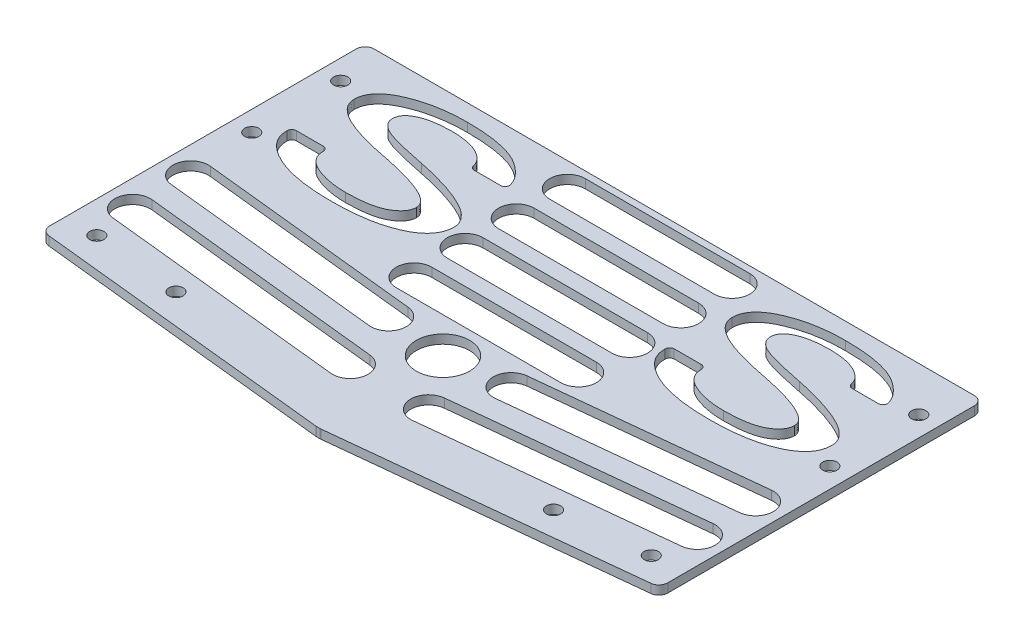
SolidWorks part; units mm, degrees
material "Thornel Mat VMA"
ref_plane "前视基准面" through (0, 0, 0) normal (0, 0, 1) x (1, 0, 0)
ref_plane "上视基准面" through (0, 0, 0) normal (0, 1, 0) x (1, 0, 0)
ref_plane "右视基准面" through (0, 0, 0) normal (1, 0, 0) x (0, 0, -1)
other "Configuration Table"
sketch "草图1" plane through (0, 0, 0) normal (0, 1, 0) x (1, 0, 0)
  line L1 (-69.5, 40) -> (69.5, 40)
  line L2 (-69.5, 40) -> (-69.5, -40)
  line L3 (-69.5, -40) -> (69.5, -40)
  line L4 (69.5, 40) -> (69.5, -40)
  line L5 (-69.5, 40) -> (69.5, -40) construction
  line L6 (-69.5, -40) -> (69.5, 40) construction
  point P0 (0, 0)
  dimension "D1" = 139
  dimension "D2" = 80
extrude "凸台-拉伸1" add sketch "草图1" along normal blind 2
sketch "草图2" plane through (0, 2, 0) normal (0, 1, 0) x (1, 0, 0)
  line L0 (0.5, -40) -> (69.5, -32.7478)
  line L1 (-69.5, -40) -> (69.5, -40) construction
  line L2 (69.5, -40) -> (69.5, 40) construction
  line L3 (69.5, -32.7478) -> (69.5, -40)
  line L4 (69.5, -40) -> (0.5, -40)
  line L5 (-69.5, -40) -> (-0.5, -40)
  line L6 (-0.5, -40) -> (-69.5, -32.7478)
  line L7 (-69.5, 40) -> (-69.5, -40) construction
  line L8 (-69.5, -32.7478) -> (-69.5, -40)
  dimension "D1" = 6
  dimension "D2" = 69
extrude "切除-拉伸1" cut sketch "草图2" against normal through all
sketch "草图3" plane through (0, 2, 0) normal (0, 1, 0) x (1, 0, 0)
  circle A0 centre (62.3465, -27.5028) radius 1.6
  circle A1 centre (42.456, -29.5934) radius 1.6
  circle A2 centre (-42.456, -29.5934) radius 1.6
  circle A3 centre (-62.3465, -27.5028) radius 1.6
  dimension "D1" = 3.2
extrude "切除-拉伸2" cut sketch "草图3" against normal blind 10
sketch "草图4" plane through (0, 2, 0) normal (0, 1, 0) x (1, 0, 0)
  line L0 (0, -45.4013) -> (0, 45.8413) construction
  line L1 (-63.5, -18.2958) -> (-8.8013, -24.0449) construction
  line L2 (-63.0819, -14.3177) -> (-8.3832, -20.0668)
  line L3 (-63.9181, -22.2739) -> (-9.2194, -28.023)
  line L4 (-63.5, -5.2242) -> (-13.7739, -10.4506) construction
  line L5 (-63.0819, -1.2461) -> (-13.3558, -6.4725)
  line L6 (-63.9181, -9.2023) -> (-14.192, -14.4287)
  line L7 (-56.5, 7.1117) -> (-18.7082, 3.1396) construction
  line L8 (-56.0819, 11.0898) -> (-18.2901, 7.1177) construction
  line L9 (-56.9181, 3.1336) -> (-19.1263, -0.8385) construction
  line L10 (-56.5, 20.1833) -> (-28.6534, 17.2565) construction
  line L11 (-56.0819, 24.1614) -> (-28.2353, 21.2346) construction
  line L12 (-56.9181, 16.2052) -> (-29.0715, 13.2784) construction
  line L13 (-0.5, -40) -> (-69.5, -32.7478) construction
  line L14 (-69.5, 40) -> (-69.5, -32.7478) construction
  line L15 (-56.5, 33.2549) -> (-38.5986, 31.3734) construction
  line L16 (-56.0819, 37.233) -> (-38.1805, 35.3515) construction
  line L17 (-56.9181, 29.2768) -> (-39.0167, 27.3953) construction
  line L18 (63.5, -18.2958) -> (8.8013, -24.0449) construction
  line L19 (63.0819, -14.3177) -> (8.3832, -20.0668)
  line L20 (63.9181, -22.2739) -> (9.2194, -28.023)
  line L21 (63.5, -5.2242) -> (13.7739, -10.4506) construction
  line L22 (63.0819, -1.2461) -> (13.3558, -6.4725)
  line L23 (63.9181, -9.2023) -> (14.192, -14.4287)
  line L24 (56.5, 7.1117) -> (18.7082, 3.1396) construction
  line L25 (56.0819, 11.0898) -> (18.2901, 7.1177) construction
  line L26 (56.9181, 3.1336) -> (19.1263, -0.8385) construction
  line L27 (56.5, 20.1833) -> (28.6534, 17.2565) construction
  line L28 (56.0819, 24.1614) -> (28.2353, 21.2346) construction
  line L29 (56.9181, 16.2052) -> (29.0715, 13.2784) construction
  line L30 (56.5, 33.2549) -> (38.5986, 31.3734) construction
  line L31 (56.0819, 37.233) -> (38.1805, 35.3515) construction
  line L32 (56.9181, 29.2768) -> (39.0167, 27.3953) construction
  line L33 (-33.9999, 37) -> (0, -11.2616)
  line L34 (0, -11.2616) -> (33.9999, 37)
  line L35 (33.9999, 37) -> (-33.9999, 37)
  line L36 (16.9085, 28) -> (-16.9085, 28)
  line L37 (-16.9085, 28) -> (0, 3.999)
  line L38 (0, 3.999) -> (16.9085, 28)
  line L39 (-3, 37) -> (-3, 28)
  line L40 (3, 37) -> (3, 28)
  line L41 (-18.7277, 15.3217) -> (-11.5427, 20.3835)
  line L42 (-15.2722, 10.4167) -> (-8.0872, 15.4784)
  line L43 (15.2722, 10.4167) -> (8.0872, 15.4784)
  line L44 (18.7277, 15.3217) -> (11.5427, 20.3835)
  line L45 (38.5986, 31.3734) -> (18.7082, 3.1396) construction
  line L46 (69.5, 40) -> (-69.5, 40) construction
  line L47 (16.9999, 12.8692) -> (9.8149, 17.9309) construction
  line L48 (8.4542, 15.9995) -> (-16.9085, 28)
  line L49 (-8.4542, 15.9995) -> (16.9085, 28)
  arc A0 (-63.0819, -14.3177) -> (-63.9181, -22.2739) centre (-63.5, -18.2958) ccw
  arc A1 (-9.2194, -28.023) -> (-8.3832, -20.0668) centre (-8.8013, -24.0449) ccw
  arc A2 (-63.0819, -1.2461) -> (-63.9181, -9.2023) centre (-63.5, -5.2242) ccw
  arc A3 (-14.192, -14.4287) -> (-13.3558, -6.4725) centre (-13.7739, -10.4506) ccw
  arc A4 (-56.0819, 11.0898) -> (-56.9181, 3.1336) centre (-56.5, 7.1117) ccw construction
  arc A5 (-19.1263, -0.8385) -> (-18.2901, 7.1177) centre (-18.7082, 3.1396) ccw construction
  arc A6 (-56.0819, 24.1614) -> (-56.9181, 16.2052) centre (-56.5, 20.1833) ccw construction
  arc A7 (-29.0715, 13.2784) -> (-28.2353, 21.2346) centre (-28.6534, 17.2565) ccw construction
  arc A8 (-56.0819, 37.233) -> (-56.9181, 29.2768) centre (-56.5, 33.2549) ccw construction
  arc A9 (-39.0167, 27.3953) -> (-38.1805, 35.3515) centre (-38.5986, 31.3734) ccw construction
  arc A10 (63.0819, -14.3177) -> (63.9181, -22.2739) centre (63.5, -18.2958) cw
  arc A11 (9.2194, -28.023) -> (8.3832, -20.0668) centre (8.8013, -24.0449) cw
  arc A12 (63.0819, -1.2461) -> (63.9181, -9.2023) centre (63.5, -5.2242) cw
  arc A13 (14.192, -14.4287) -> (13.3558, -6.4725) centre (13.7739, -10.4506) cw
  arc A14 (56.0819, 11.0898) -> (56.9181, 3.1336) centre (56.5, 7.1117) cw construction
  arc A15 (19.1263, -0.8385) -> (18.2901, 7.1177) centre (18.7082, 3.1396) cw construction
  arc A16 (56.0819, 24.1614) -> (56.9181, 16.2052) centre (56.5, 20.1833) cw construction
  arc A17 (29.0715, 13.2784) -> (28.2353, 21.2346) centre (28.6534, 17.2565) cw construction
  arc A18 (56.0819, 37.233) -> (56.9181, 29.2768) centre (56.5, 33.2549) cw construction
  arc A19 (39.0167, 27.3953) -> (38.1805, 35.3515) centre (38.5986, 31.3734) cw construction
  ellipse E0 centre (0, 19.9997) end of major axis (9.5, 19.9997) minor radius 6
  point P5 (-36.1506, -21.1703)
  point P10 (-38.637, -7.8374)
  point P17 (-37.6041, 5.1256)
  point P24 (-42.5767, 18.7199)
  point P35 (-47.5493, 32.3141)
  point P45 (36.1506, -21.1703)
  point P52 (38.637, -7.8374)
  point P59 (37.6041, 5.1256)
  point P66 (42.5767, 18.7199)
  point P73 (47.5493, 32.3141)
  dimension "D2" = 4
  dimension "D1" = 6
  dimension "D3" = 15
  dimension "D4" = 13
  dimension "D5" = 13
  dimension "D6" = 13
  dimension "D7" = 55
  dimension "D8" = 50
  dimension "D9" = 38
  dimension "D10" = 28
  dimension "D11" = 18
  dimension "D12" = 13
  dimension "D13" = 3
  dimension "D14" = 9
  dimension "D15" = 8.7889
  dimension "D16" = 3
  dimension "D17" = 6
  dimension "D18" = 6
  dimension "D19" = 12
  dimension "D20" = 19
  dimension "D21" = 13
extrude "切除-拉伸3" cut sketch "草图4" against normal blind 10 contours L3 A1 L2 A0 | L6 A3 L5 A2 | L9 A5 L8 A4 | L12 A7 L11 A6 | A11 L20 A10 L19 | A13 L23 A12 L22 | A15 L26 A14 L25 | A17 L29 A16 L28 | A19 L32 A18 L31 | L16 A9 L17 A8
sketch "草图5" [suppressed] plane through (0, 2, 0) normal (0, 1, 0) x (1, 0, 0)
  line L0 (-33.2954, 36) -> (33.2954, 36)
  line L1 (33.2954, 36) -> (0, -11.2616)
  line L2 (0, -11.2616) -> (-33.2954, 36)
  line L3 (0, -16.1685) -> (0, 46.4775) construction
  line L4 (18.7082, 3.1396) -> (38.5986, 31.3734) construction
  line L5 (69.5, 40) -> (-69.5, 40) construction
  line L6 (-1.635, 33.6792) -> (-14.4272, 15.521)
  line L7 (-12.7922, 12.3692) -> (12.7922, 12.3692)
  line L8 (14.4272, 15.521) -> (1.635, 33.6792)
  line L9 (22.0183, 36) -> (27.6568, 27.9963)
  line L10 (12.2324, 36) -> (22.7639, 21.0509)
  line L13 (0, 41.209) -> (-22.4309, 9.3692)
  line L14 (-22.4309, 9.3692) -> (22.4309, 9.3692)
  line L15 (22.4309, 9.3692) -> (0, 41.209)
  line L17 (-22.0183, 36) -> (-27.6568, 27.9963)
  line L18 (-22.0183, 36) -> (-27.6568, 27.9963)
  line L19 (-12.2324, 36) -> (-22.7639, 21.0509)
  line L20 (-11.0118, 4.3692) -> (11.0118, 4.3692)
  line L21 (-5.3758, -3.6308) -> (5.3758, -3.6308)
  arc A0 (12.7922, 12.3692) -> (14.4272, 15.521) centre (12.7922, 14.3692) ccw
  arc A1 (-1.635, 33.6792) -> (1.635, 33.6792) centre (0, 32.5273) cw
  arc A2 (-14.4272, 15.521) -> (-12.7922, 12.3692) centre (-12.7922, 14.3692) ccw
  arc A3 (28.2353, 21.2346) -> (29.0715, 13.2784) centre (28.6534, 17.2565) ccw construction
  point P31 (16.6477, 12.3692)
  point P34 (0, 36)
  point P37 (-16.6477, 12.3692)
  dimension "D9" = 2
  dimension "D1" = 4
  dimension "D2" = 3
  dimension "D3" = 8
  dimension "D5" = 10
  dimension "D7" = 3
  dimension "D8" = 3
  dimension "D10" = 8
  dimension "D13" = 8
sketch "草图7" plane through (0, 2, 0) normal (0, 1, 0) x (1, 0, 0)
  line L0 (69.5, -32.7478) -> (69.5, 40) construction
  line L1 (69.5, 40) -> (-69.5, 40) construction
  line L2 (0, -47.5793) -> (0, 49.9198) construction
  circle A0 centre (65, 30) radius 1.6
  circle A1 centre (65, 10) radius 1.6
  circle A2 centre (-65, 10) radius 1.6
  circle A3 centre (-65, 30) radius 1.6
  circle A4 centre (0, -12) radius 6
  dimension "D2" = 4.5
  dimension "D4" = 3.2
  dimension "D5" = 12
  dimension "D1" = 20
  dimension "D3" = 10
  dimension "D6" = 12
extrude "切除-拉伸6" cut sketch "草图7" against normal blind 10
sketch "草图8" plane through (0, 2, 0) normal (0, 1, 0) x (1, 0, 0)
  line L2 (-69.5, 40) -> (-69.5, -32.7478) construction
  line L3 (69.5, 40) -> (-69.5, 40) construction
  text T0 "S" font "黑体" height 30
  text T1 "S" font "黑体" height 30
  point P2 (-61.6496, 12.7033)
  point P3 (0, 0)
  point P4 (-62.0653, 8.2683)
  point P7 (0, 0)
  point P9 (19.1491, 5)
  point P11 (-59.5, 5)
  point P12 (-59.5, 5)
  point P13 (2.3309, 5)
  point P14 (0, 0)
  dimension "D1" = 5
  dimension "D2" = 35
  dimension "D3" = 85
extrude "切除-拉伸7" cut sketch "草图8" against normal blind 10
sketch "草图9" plane through (0, 2, 0) normal (0, 1, 0) x (1, 0, 0)
  line L0 (-18.5, 0) -> (18.5, 0) construction
  line L1 (-18.5, 4) -> (18.5, 4)
  line L2 (-18.5, -4) -> (18.5, -4)
  line L3 (-18.5, 11.5) -> (18.5, 11.5) construction
  line L4 (-18.5, 15.5) -> (18.5, 15.5)
  line L5 (-18.5, 7.5) -> (18.5, 7.5)
  line L6 (-18.5, 23) -> (18.5, 23) construction
  line L7 (-18.5, 27) -> (18.5, 27)
  line L8 (-18.5, 19) -> (18.5, 19)
  line L9 (-18.5, 34.5) -> (18.5, 34.5) construction
  line L10 (-18.5, 38.5) -> (18.5, 38.5)
  line L11 (-18.5, 30.5) -> (18.5, 30.5)
  arc A0 (-18.5, 4) -> (-18.5, -4) centre (-18.5, 0) ccw
  arc A1 (18.5, -4) -> (18.5, 4) centre (18.5, 0) ccw
  arc A2 (13.3558, -6.4725) -> (14.192, -14.4287) centre (13.7739, -10.4506) ccw construction
  arc A3 (-18.5, 15.5) -> (-18.5, 7.5) centre (-18.5, 11.5) ccw
  arc A4 (18.5, 7.5) -> (18.5, 15.5) centre (18.5, 11.5) ccw
  arc A5 (-18.5, 27) -> (-18.5, 19) centre (-18.5, 23) ccw
  arc A6 (18.5, 19) -> (18.5, 27) centre (18.5, 23) ccw
  arc A7 (-18.5, 38.5) -> (-18.5, 30.5) centre (-18.5, 34.5) ccw
  arc A8 (18.5, 30.5) -> (18.5, 38.5) centre (18.5, 34.5) ccw
  point P3 (0, 0)
  point P14 (0, 11.5)
  point P21 (0, 23)
  point P28 (0, 34.5)
  dimension "D2" = 4
  dimension "D1" = 37
  dimension "D3" = 11.5
extrude "切除-拉伸8" cut sketch "草图9" against normal blind 10
fillet "圆角1" radius 2 6 edges at (0.5, 1, 40) (-0.5, 1, 40) (-69.5, 1, 32.7478) (69.5, 1, -40) (69.5, 1, 32.7478) (-69.5, 1, -40)
fillet "圆角2" radius 1 12 edges at (-61.3421, 1, -15.3509) (-53.2719, 1, -15.3509) (-25.5526, 1, -27.6316) (-33.6228, 1, -27.6316) (23.6579, 1, -15.3509) (31.7281, 1, -15.3509) (59.4474, 1, -27.6316) (51.3772, 1, -27.6316)
